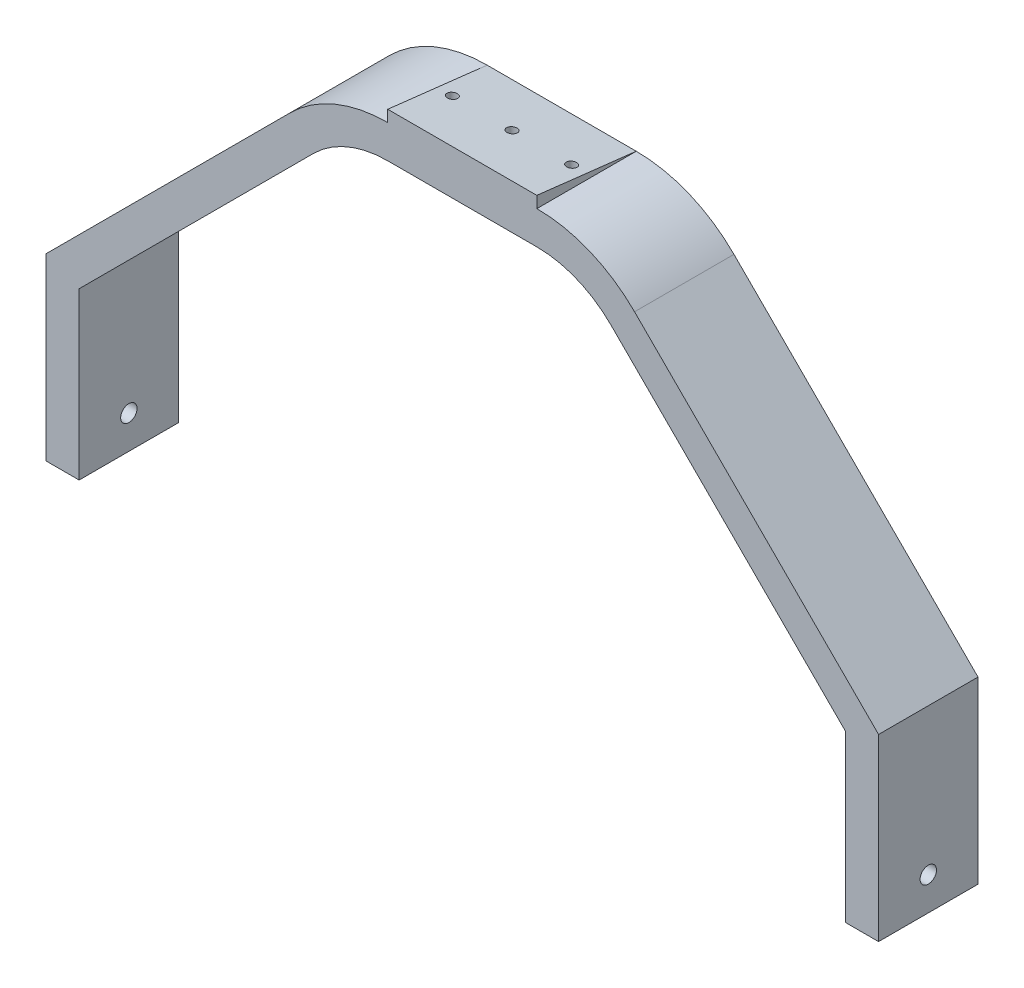
SolidWorks part; units mm, degrees
ref_plane "Alzado" through (0, 0, 0) normal (0, 0, 1) x (1, 0, 0)
ref_plane "Planta" through (0, 0, 0) normal (0, 1, 0) x (1, 0, 0)
ref_plane "Vista lateral" through (0, 0, 0) normal (1, 0, 0) x (0, 0, -1)
sketch "Croquis1" plane through (0, 0, 0) normal (0, 0, 1) x (1, 0, 0)
  line L0 (-22.5, -36.6894) -> (-68.1161, -36.6894) construction
  line L1 (-22.5, -5) -> (22.5, -5)
  line L3 (-22.5, 5) -> (22.5, 5)
  line L5 (0, -5) -> (0, 9.8205) construction
  line L6 (-51.9789, -7.2106) -> (-122.6896, -77.9212)
  line L7 (-68.1161, -36.6894) -> (22.5, -36.6894) construction
  line L8 (-22.5, -36.6894) -> (-55.2569, -3.9326) construction
  line L9 (-44.9078, -14.2816) -> (-115.6185, -84.9923)
  line L12 (-115.6185, -84.9923) -> (-115.6185, -134.9923)
  line L14 (22.5, -36.6894) -> (55.2569, -3.9326) construction
  line L15 (68.1161, -36.6894) -> (-22.5, -36.6894) construction
  line L16 (22.5, -36.6894) -> (68.1161, -36.6894) construction
  line L23 (-115.6185, -134.9923) -> (-125.6185, -134.9923)
  line L24 (-125.6185, -134.9923) -> (-125.6185, -80.8502)
  line L25 (-122.6896, -77.9212) -> (-125.6185, -80.8502)
  line L26 (44.9078, -14.2816) -> (115.6185, -84.9923)
  line L27 (51.9789, -7.2106) -> (122.6896, -77.9212)
  line L28 (122.6896, -77.9212) -> (125.6185, -80.8502)
  line L29 (125.6185, -134.9923) -> (125.6185, -80.8502)
  line L30 (115.6185, -134.9923) -> (125.6185, -134.9923)
  line L31 (115.6185, -84.9923) -> (115.6185, -134.9923)
  arc A0 (-22.5, -5) -> (-44.9078, -14.2816) centre (-22.5, -36.6894) ccw
  arc A1 (-22.5, 5) -> (-51.9789, -7.2106) centre (-22.5, -36.6894) ccw
  arc A2 (22.5, 5) -> (51.9789, -7.2106) centre (22.5, -36.6894) cw
  arc A3 (22.5, -5) -> (44.9078, -14.2816) centre (22.5, -36.6894) cw
  point P0 (0, 0)
extrude "Saliente-Extruir1" add sketch "Croquis1" along normal blind 30
sketch "Croquis3" plane through (-125.6185, 0, 0) normal (-1, 0, 0) x (0, 0, 1)
  line L0 (30, -134.9923) -> (0, -134.9923) construction
  circle A0 centre (15, -124.9923) radius 2.475
  dimension "D1" = 10
extrude "Cortar-Extruir1" cut sketch "Croquis3" against normal through all
sketch "Croquis4" plane through (0, 5, 0) normal (0, 1, 0) x (1, 0, 0)
  circle A1 centre (0, -15) radius 1.5
  circle A3 centre (18, -15) radius 1.5
  circle A4 centre (-18, -15) radius 1.5
  point P9 (0, -15)
extrude "Cortar-Extruir2" cut sketch "Croquis4" against normal through all
sketch "Croquis5" plane through (0, 5, 0) normal (0, 1, 0) x (1, 0, 0)
  line L1 (-22.5, 0) -> (22.5, 0)
  line L2 (-22.5, 0) -> (-22.5, -30)
  line L3 (-22.5, -30) -> (22.5, -30)
  line L4 (22.5, 0) -> (22.5, -30)
extrude "Saliente-Extruir2" add sketch "Croquis5" along normal blind 12
sketch "Croquis6" plane through (22.5, 0, 0) normal (1, 0, 0) x (0, 0, -1)
  line L0 (0, 5) -> (-30, 8.4711)
  line L1 (-30, 17) -> (-30, 5) construction
  line L4 (-30, 8.4711) -> (-30, 19.9231)
  line L5 (-30, 19.9231) -> (0, 19.9231)
  line L6 (0, 19.9231) -> (0, 5)
extrude "Cortar-Extruir3" cut sketch "Croquis6" against normal through all
sketch "Croquis7" plane through (0, -5, 0) normal (0, -1, 0) x (1, 0, 0)
  circle A0 centre (0, 15) radius 1.5
  circle A1 centre (-18, 15) radius 1.5
  circle A2 centre (18, 15) radius 1.5
extrude "Cortar-Extruir4" cut sketch "Croquis7" against normal through all
